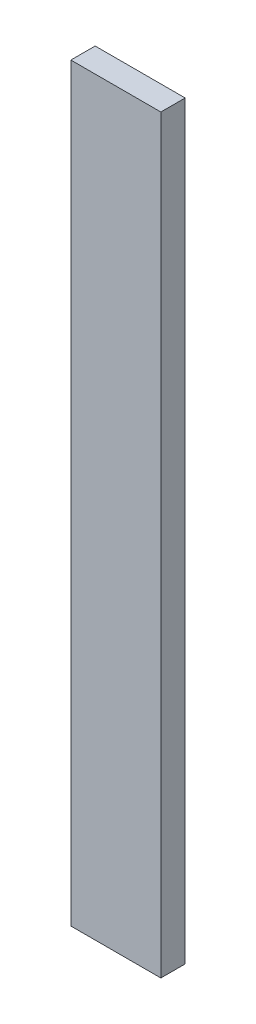
SolidWorks part; units mm, degrees
ref_plane "Plan de face" through (0, 0, 0) normal (0, 0, 1) x (1, 0, 0)
ref_plane "Plan de dessus" through (0, 0, 0) normal (0, 1, 0) x (1, 0, 0)
ref_plane "Plan de droite" through (0, 0, 0) normal (1, 0, 0) x (0, 0, -1)
sketch "Esquisse1" plane through (0, 0, 0) normal (0, 0, 1) x (1, 0, 0)
  line L1 (0, 0) -> (30, 0)
  line L2 (0, 0) -> (0, 250)
  line L3 (0, 250) -> (30, 250)
  line L4 (30, 0) -> (30, 250)
  dimension "D1" = 30
  dimension "D2" = 250
extrude "Boss.-Extru.1" add sketch "Esquisse1" along normal blind 8.1
